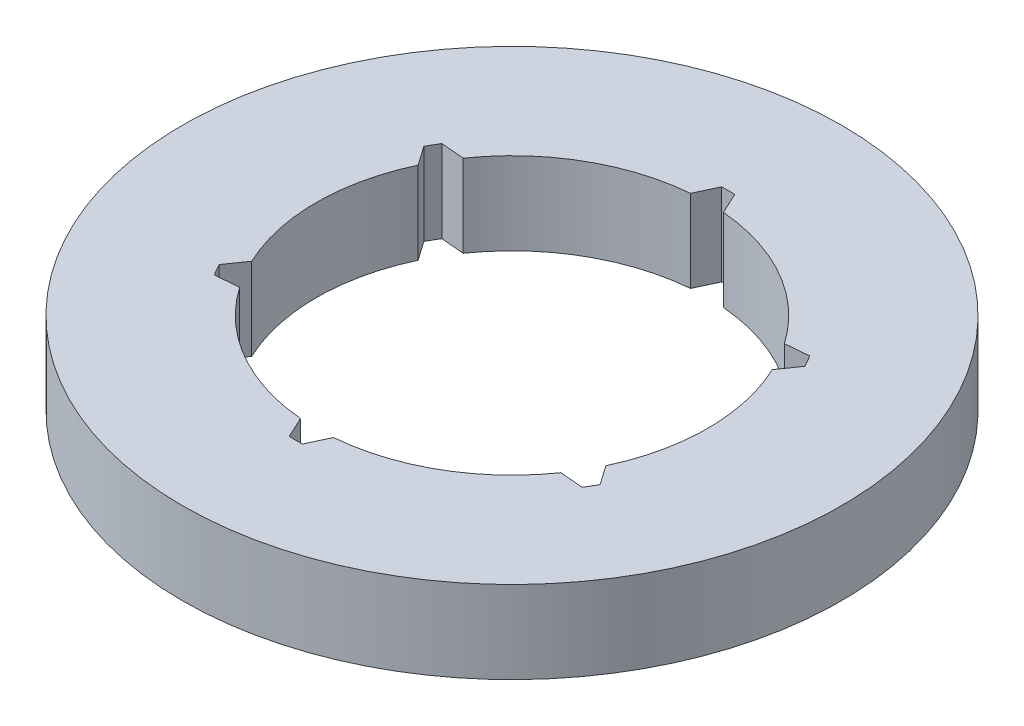
SolidWorks part; units mm, degrees
ref_plane "Front Plane" through (0, 0, 0) normal (0, 0, 1) x (1, 0, 0)
ref_plane "Top Plane" through (0, 0, 0) normal (0, 1, 0) x (1, 0, 0)
ref_plane "Right Plane" through (0, 0, 0) normal (1, 0, 0) x (0, 0, -1)
sketch "Sketch1" plane through (0, 0, 0) normal (0, 1, 0) x (1, 0, 0)
  line L0 (0, 0) -> (0, 34.5685) construction
  line L1 (-2, 26.1737) -> (-2, 23.6656) construction
  line L2 (-2, 23.6656) -> (-0.8006, 26.2378)
  line L3 (2, 23.6656) -> (0.8006, 26.2378)
  line L4 (19.495, 13.5649) -> (22.3223, 13.8122)
  line L5 (21.495, 10.1008) -> (23.1229, 12.4256)
  line L6 (21.495, -10.1008) -> (23.1229, -12.4256)
  line L7 (19.495, -13.5649) -> (22.3223, -13.8122)
  line L8 (2, -23.6656) -> (0.8006, -26.2378)
  line L9 (-2, -23.6656) -> (-0.8006, -26.2378)
  line L10 (-19.495, -13.5649) -> (-22.3223, -13.8122)
  line L11 (-21.495, -10.1008) -> (-23.1229, -12.4256)
  line L12 (-21.495, 10.1008) -> (-23.1229, 12.4256)
  line L13 (-19.495, 13.5649) -> (-22.3223, 13.8122)
  arc A0 (-2, 23.6656) -> (-19.495, 13.5649) centre (0, 0) ccw
  arc A1 (0.8006, 26.2378) -> (-0.8006, 26.2378) centre (0, 0) ccw
  arc A2 (23.1229, 12.4256) -> (22.3223, 13.8122) centre (0, 0) ccw
  arc A3 (22.3223, -13.8122) -> (23.1229, -12.4256) centre (0, 0) ccw
  arc A4 (-0.8006, -26.2378) -> (0.8006, -26.2378) centre (0, 0) ccw
  arc A5 (-23.1229, -12.4256) -> (-22.3223, -13.8122) centre (0, 0) ccw
  arc A6 (-22.3223, 13.8122) -> (-23.1229, 12.4256) centre (0, 0) ccw
  arc A7 (-21.495, 10.1008) -> (-21.495, -10.1008) centre (0, 0) ccw
  arc A8 (19.495, 13.5649) -> (2, 23.6656) centre (0, 0) ccw
  arc A9 (21.495, -10.1008) -> (21.495, 10.1008) centre (0, 0) ccw
  arc A10 (2, -23.6656) -> (19.495, -13.5649) centre (0, 0) ccw
  arc A11 (-19.495, -13.5649) -> (-2, -23.6656) centre (0, 0) ccw
  circle A12 centre (0, 0) radius 40
  point P30 (0, 0)
  dimension "D1" = 47.5
  dimension "D2" = 52.5
  dimension "D6" = 80
  dimension "D3" = 2
  dimension "D4" = 25
  dimension "D5" = 6
extrude "Boss-Extrude1" add sketch "Sketch1" along normal blind 10
sketch "4,5,6" plane through (0, 10, 0) normal (0, 1, 0) x (1, 0, 0)
  line L0 (0, 23.5241) -> (0, 36.2824) construction
  line L1 (2.5, 35.9681) -> (2.5, 28.892) construction
  line L2 (2.5, 28.892) -> (1.0105, 32.9845)
  line L3 (-2.5, 28.892) -> (-1.0105, 32.9845)
  line L4 (23.7712, 16.6111) -> (28.0602, 17.3673)
  line L5 (26.2712, 12.281) -> (29.0707, 15.6172)
  line L6 (26.2712, -12.281) -> (29.0707, -15.6172)
  line L7 (23.7712, -16.6111) -> (28.0602, -17.3673)
  line L8 (2.5, -28.892) -> (1.0105, -32.9845)
  line L9 (-2.5, -28.892) -> (-1.0105, -32.9845)
  line L10 (-23.7712, -16.6111) -> (-28.0602, -17.3673)
  line L11 (-26.2712, -12.281) -> (-29.0707, -15.6172)
  line L12 (-26.2712, 12.281) -> (-29.0707, 15.6172)
  line L13 (-23.7712, 16.6111) -> (-28.0602, 17.3673)
  arc A0 (2.5, 28.892) -> (-2.5, 28.892) centre (0, 0) ccw
  arc A1 (1.0105, 32.9845) -> (-1.0105, 32.9845) centre (0, 0) ccw
  arc A2 (26.2712, 12.281) -> (23.7712, 16.6111) centre (0, 0) ccw
  arc A3 (29.0707, 15.6172) -> (28.0602, 17.3673) centre (0, 0) ccw
  arc A4 (23.7712, -16.6111) -> (26.2712, -12.281) centre (0, 0) ccw
  arc A5 (28.0602, -17.3673) -> (29.0707, -15.6172) centre (0, 0) ccw
  arc A6 (-2.5, -28.892) -> (2.5, -28.892) centre (0, 0) ccw
  arc A7 (-1.0105, -32.9845) -> (1.0105, -32.9845) centre (0, 0) ccw
  arc A8 (-26.2712, -12.281) -> (-23.7712, -16.6111) centre (0, 0) ccw
  arc A9 (-29.0707, -15.6172) -> (-28.0602, -17.3673) centre (0, 0) ccw
  arc A10 (-23.7712, 16.6111) -> (-26.2712, 12.281) centre (0, 0) ccw
  arc A11 (-28.0602, 17.3673) -> (-29.0707, 15.6172) centre (0, 0) ccw
  point P31 (0, 0)
  dimension "D1" = 58
  dimension "D2" = 66
  dimension "D3" = 2.5
  dimension "D4" = 20
  dimension "D5" = 6
sketch "1,2,3" plane through (0, 10, 0) normal (0, 1, 0) x (1, 0, 0)
  line L0 (0, 18.8714) -> (0, 44.4172) construction
  line L1 (2.5, 34.9106) -> (2.5, 30.899) construction
  line L2 (2.5, 30.899) -> (1.0127, 34.9853)
  line L3 (-2.5, 30.899) -> (-1.0127, 34.9853)
  line L4 (25.5093, 17.6146) -> (29.7918, 18.3697)
  line L5 (28.0093, 13.2845) -> (30.8045, 16.6156)
  line L6 (28.0093, -13.2845) -> (30.8045, -16.6156)
  line L7 (25.5093, -17.6146) -> (29.7918, -18.3697)
  line L8 (2.5, -30.899) -> (1.0127, -34.9853)
  line L9 (-2.5, -30.899) -> (-1.0127, -34.9853)
  line L10 (-25.5093, -17.6146) -> (-29.7918, -18.3697)
  line L11 (-28.0093, -13.2845) -> (-30.8045, -16.6156)
  line L12 (-28.0093, 13.2845) -> (-30.8045, 16.6156)
  line L13 (-25.5093, 17.6146) -> (-29.7918, 18.3697)
  arc A0 (2.5, 30.899) -> (-2.5, 30.899) centre (0, 0) ccw
  arc A1 (1.0127, 34.9853) -> (-1.0127, 34.9853) centre (0, 0) ccw
  arc A2 (28.0093, 13.2845) -> (25.5093, 17.6146) centre (0, 0) ccw
  arc A3 (30.8045, 16.6156) -> (29.7918, 18.3697) centre (0, 0) ccw
  arc A4 (25.5093, -17.6146) -> (28.0093, -13.2845) centre (0, 0) ccw
  arc A5 (29.7918, -18.3697) -> (30.8045, -16.6156) centre (0, 0) ccw
  arc A6 (-2.5, -30.899) -> (2.5, -30.899) centre (0, 0) ccw
  arc A7 (-1.0127, -34.9853) -> (1.0127, -34.9853) centre (0, 0) ccw
  arc A8 (-28.0093, -13.2845) -> (-25.5093, -17.6146) centre (0, 0) ccw
  arc A9 (-30.8045, -16.6156) -> (-29.7918, -18.3697) centre (0, 0) ccw
  arc A10 (-25.5093, 17.6146) -> (-28.0093, 13.2845) centre (0, 0) ccw
  arc A11 (-29.7918, 18.3697) -> (-30.8045, 16.6156) centre (0, 0) ccw
  point P32 (0, 0)
  dimension "D1" = 62
  dimension "D2" = 70
  dimension "D3" = 2.5
  dimension "D4" = 20
  dimension "D5" = 6
